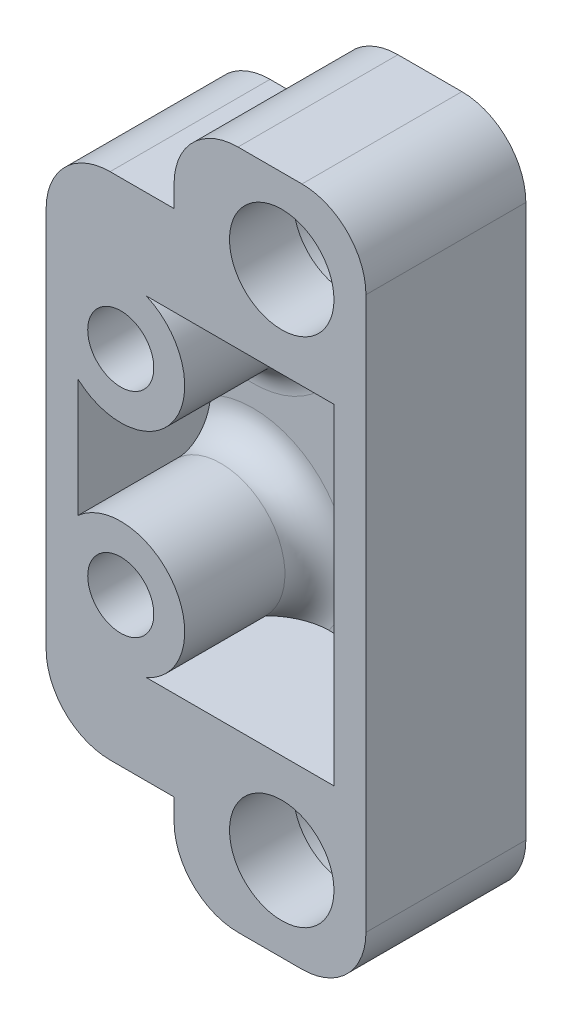
SolidWorks part; units mm, degrees
ref_plane "Front Plane" through (0, 0, 0) normal (0, 0, 1) x (1, 0, 0)
ref_plane "Top Plane" through (0, 0, 0) normal (0, 1, 0) x (1, 0, 0)
ref_plane "Right Plane" through (0, 0, 0) normal (1, 0, 0) x (0, 0, -1)
sketch "Sketch1" plane through (0, 0, 0) normal (0, 0, 1) x (1, 0, 0)
  line L0 (-10.2404, 15.95) -> (-10.2404, -15.95)
  line L1 (-6.2904, -12) -> (6.2904, -12)
  line L2 (-6.2904, -12) -> (-6.2904, 12)
  line L3 (-6.2904, 12) -> (6.2904, 12)
  line L4 (6.2904, -12) -> (6.2904, 12)
  line L5 (-6.2904, -12) -> (6.2904, 12) construction
  line L6 (-6.2904, 12) -> (6.2904, -12) construction
  line L7 (-8.7404, 14.45) -> (8.7404, 14.45)
  line L8 (-8.7404, 14.45) -> (-8.7404, -14.45)
  line L9 (-8.7404, -14.45) -> (8.7404, -14.45)
  line L10 (8.7404, 14.45) -> (8.7404, -14.45)
  line L11 (-8.7404, 14.45) -> (8.7404, -14.45) construction
  line L12 (-8.7404, -14.45) -> (8.7404, 14.45) construction
  line L13 (-10.2404, -15.95) -> (10.2404, -15.95)
  line L14 (10.2404, 15.95) -> (10.2404, -15.95)
  line L15 (-10.2404, 15.95) -> (10.2404, 15.95)
  circle A0 centre (6.2904, 12) radius 2.45
  circle A1 centre (6.2904, -12) radius 2.45
  point P0 (0, 0)
  point P8 (0, 0)
  dimension "D2" = 4.9
  dimension "D3" = 4.9
  dimension "D1" = 24
  dimension "D5" = 31.9
  dimension "D4" = 1.5
extrude "Boss-Extrude1" add sketch "Sketch1" along normal blind 7.5 contours L15 L0 L13 L14 L7 L10 L9 L8 | A0 L10 L7 | A1 L1 L2 L3 A0 L7 L8 L9 | A1 L10 A0 L4 | A1 L4 A0 L3 L2 L1 | A1 L9 L10
sketch "Sketch2" plane through (0, 0, 7.5) normal (0, 0, 1) x (1, 0, 0)
  line L0 (10.2404, 15.95) -> (8.7404, 15.95)
  line L1 (-10.2404, 15.95) -> (10.2404, 15.95) construction
  line L2 (8.7404, 15.95) -> (8.7404, -15.95)
  line L3 (-10.2404, -15.95) -> (10.2404, -15.95) construction
  line L4 (8.7404, 0) -> (-10.2404, 0)
  line L5 (-10.2404, 15.95) -> (-10.2404, -15.95) construction
  line L7 (-10.2404, -9.35) -> (8.7404, -9.35)
  line L8 (-10.2404, -9.35) -> (-10.2404, 9.35)
  line L9 (-10.2404, 9.35) -> (8.7404, 9.35)
  line L10 (8.7404, -9.35) -> (8.7404, 9.35)
  line L11 (-10.2404, -9.35) -> (8.7404, 9.35) construction
  line L12 (-10.2404, 9.35) -> (8.7404, -9.35) construction
  point P12 (-0.75, 0)
  line M11 (-10.2404, 15.95) -> (-10.2404, -15.95)
  dimension "D1" = 1.5
  dimension "D2" = 18.7
extrude "Cut-Extrude1" cut sketch "Sketch2" against normal blind 6.2 contours L9 L4 L2 M11 | L7 L2 L4 M11
sketch "Sketch3" plane through (0, 0, 1.3) normal (0, 0, 1) x (1, 0, 0)
  line L0 (10.2404, 0) -> (-1.2596, 0)
  line L1 (10.2404, 15.95) -> (10.2404, -15.95) construction
  line L2 (-1.2596, -5) -> (-1.2596, 5)
  circle A0 centre (-1.2596, 5) radius 1.55
  circle A1 centre (-1.2596, -5) radius 1.55
  circle A2 centre (-1.2596, 5) radius 3
  circle A3 centre (-1.2596, -5) radius 3
  point P7 (-1.2596, 0)
  dimension "D3" = 3.1
  dimension "D4" = 3.1
  dimension "D5" = 6
  dimension "D6" = 6
  dimension "D1" = 10
  dimension "D2" = 11.5
sketch "Sketch5" plane through (0, 0, 7.5) normal (0, 0, 1) x (1, 0, 0)
  line L0 (10.2404, 15.95) -> (-4.7596, 15.95)
  line L1 (-10.2404, 15.95) -> (10.2404, 15.95) construction
  line L3 (-4.7596, 15.95) -> (-10.2404, 15.95)
  line L4 (-4.7596, 15.95) -> (-4.7596, -15.95)
  line L5 (-4.7596, -15.95) -> (-10.2404, -15.95)
  line L6 (-10.2404, 15.95) -> (-10.2404, -15.95)
  line M6 (-10.2404, 15.95) -> (-10.2404, 9.35)
  line M7 (-10.2404, 9.35) -> (8.7404, 9.35)
  line M13 (10.2404, 15.95) -> (-10.2404, 15.95)
  dimension "D1" = 15
extrude "Cut-Extrude2" cut sketch "Sketch5" against normal up to surface (7.5 mm away) contours L4 M13 M6 M7
extrude "Boss-Extrude4" add sketch "Sketch3" along normal up to surface (6.2 mm away) up to face at (8.7404, 12, 7.5)
sketch "Sketch6" plane through (0, 0, 7.5) normal (0, 0, 1) x (1, 0, 0)
  line L0 (8.7404, 0) -> (10.2404, 0)
  line L1 (8.7404, 9.35) -> (8.7404, -9.35) construction
  line L2 (10.2404, 15.95) -> (10.2404, -15.95) construction
  line L8 (8.7404, -7.75) -> (10.2404, -7.75)
  line L9 (8.7404, -7.75) -> (8.7404, 7.75)
  line L10 (8.7404, 7.75) -> (10.2404, 7.75)
  line L11 (10.2404, -7.75) -> (10.2404, 7.75)
  line L12 (8.7404, -7.75) -> (10.2404, 7.75) construction
  line L13 (8.7404, 7.75) -> (10.2404, -7.75) construction
  point P6 (9.4904, 0)
  point P7 (9.4904, 0)
  dimension "D1" = 15.5
extrude "Cut-Extrude3" cut sketch "Sketch6" against normal up to surface (6.2 mm away)
sketch "Sketch7" plane through (0, 0, 1.3) normal (0, 0, 1) x (1, 0, 0)
  line L0 (-4.7596, -9.35) -> (8.7404, -9.35) construction
  line L1 (-4.7596, 9.35) -> (-3.2596, 9.35)
  line L2 (-4.7596, 9.35) -> (-4.7596, -9.35)
  line L3 (-4.7596, -9.35) -> (-3.2596, -9.35)
  line L4 (-3.2596, 9.35) -> (-3.2596, -9.35)
  dimension "D1" = 1.5
extrude "Boss-Extrude5" add sketch "Sketch7" along normal up to surface (6.2 mm away) contours L2 L1 L4 L3 up to face at (8.7404, 12, 7.5)
fillet "Fillet1" radius 3 2 edges at (10.2404, -15.95, 3.75) (10.2404, 15.95, 3.75)
sketch "Sketch8" plane through (0, 0, 7.5) normal (0, 0, 1) x (1, 0, 0)
  line L1 (-4.7596, 15.95) -> (1.2404, 15.95)
  line L2 (-4.7596, 15.95) -> (-4.7596, 11.95)
  line L3 (-4.7596, 11.95) -> (1.2404, 11.95)
  line L4 (1.2404, 15.95) -> (1.2404, 11.95)
  line L5 (-4.7596, -15.95) -> (1.2404, -15.95)
  line L6 (-4.7596, -15.95) -> (-4.7596, -11.95)
  line L7 (-4.7596, -11.95) -> (1.2404, -11.95)
  line L8 (1.2404, -15.95) -> (1.2404, -11.95)
  dimension "D1" = 4
  dimension "D2" = 4
  dimension "D3" = 6
  dimension "D4" = 6
extrude "Cut-Extrude4" cut sketch "Sketch8" against normal up to surface (7.5 mm away) contours L2 L1 L4 L3 | L6 L5 L8 L7 up to face at (8.7404, -12, 0)
fillet "Fillet2" radius 3 4 edges at (-4.7596, 11.95, 3.75) (1.2404, 15.95, 3.75) (1.2404, -15.95, 3.75) (-4.7596, -11.95, 3.75)
sketch "Sketch11" plane through (0, 0, 1.3) normal (0, 0, 1) x (1, 0, 0)
  line L0 (-3.2596, 7.2361) -> (-3.2596, 7.75)
  line L1 (8.7404, 7.75) -> (-0.0606, 7.75)
  line L2 (8.7404, 7.75) -> (8.7404, 9.35)
  line L3 (8.7404, 9.35) -> (-3.2596, 9.35)
  line L4 (-3.2596, 7.75) -> (-3.2596, 9.35)
  line L5 (0, 0) -> (4.7163, 0)
  line L6 (-3.2596, -7.75) -> (-3.2596, -9.35)
  line L7 (8.7404, -9.35) -> (-3.2596, -9.35)
  line L8 (8.7404, -7.75) -> (8.7404, -9.35)
  line L9 (8.7404, -7.75) -> (-0.0606, -7.75)
  line L10 (-3.2596, -7.2361) -> (-3.2596, -7.75)
  arc A0 (-0.0606, 7.75) -> (-3.2596, 7.2361) centre (-1.2596, 5) ccw
  arc A1 (-0.0606, -7.75) -> (-3.2596, -7.2361) centre (-1.2596, -5) cw
extrude "Boss-Extrude6" add sketch "Sketch11" along normal up to surface and the other way up to surface up to face at (8.7404, -12, 7.5) other way up to face at (8.7404, 12, 0)
sketch "Sketch10" plane through (0, 0, 0) normal (0, 0, -1) x (-1, 0, 0)
  circle A0 centre (-6.2904, 12) radius 3.25
  circle A1 centre (-6.2904, -12) radius 3.25
  dimension "D1" = 6.5
  dimension "D2" = 6.5
extrude "Cut-Extrude6" cut sketch "Sketch10" against normal blind 4.5
fillet "Fillet3" radius 1.5 2 edges at (1.2654, 3.38, 1.3) (1.2654, -3.38, 1.3)
sketch "Sketch12" plane through (0, 0, 1.3) normal (0, 0, 1) x (1, 0, 0)
  line L0 (-0.0606, -7.75) -> (10.2404, -7.75) construction
  line L1 (10.2404, 7.75) -> (8.7404, 7.75)
  line L2 (10.2404, 7.75) -> (10.2404, -7.75)
  line L3 (10.2404, -7.75) -> (8.7404, -7.75)
  line L4 (8.7404, 7.75) -> (8.7404, -7.75)
  dimension "D1" = 1.5
extrude "Boss-Extrude7" add sketch "Sketch12" along normal up to surface (6.2 mm away) up to face at (2.6907, 0, 7.5)
